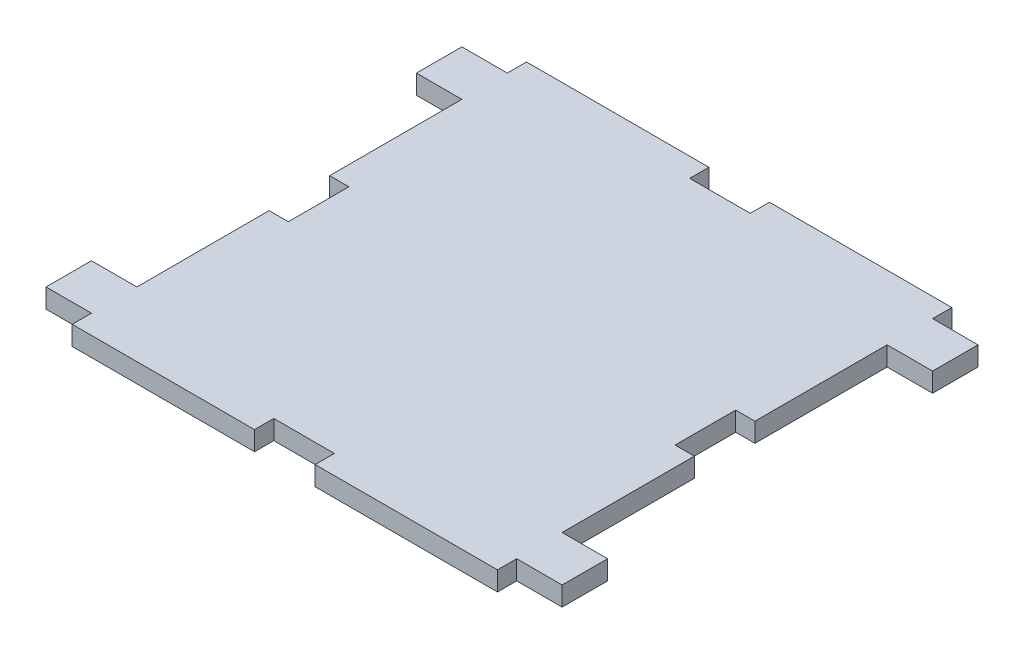
SolidWorks part; units mm, degrees
ref_plane "Front Plane" through (0, 0, 0) normal (0, 0, 1) x (1, 0, 0)
ref_plane "Top Plane" through (0, 0, 0) normal (0, 1, 0) x (1, 0, 0)
ref_plane "Right Plane" through (0, 0, 0) normal (1, 0, 0) x (0, 0, -1)
sketch "Sketch1" plane through (0, 0, 0) normal (0, 1, 0) x (1, 0, 0)
  line L0 (0, 0) -> (0, 150) construction
  line L1 (-140.4, 150) -> (140.4, 150)
  line L2 (-140.4, 150) -> (-140.4, -150)
  line L3 (-140.4, -150) -> (140.4, -150)
  line L4 (140.4, 150) -> (140.4, -150)
  line L5 (0, 0) -> (140.4, 0) construction
  line L6 (-140.4, -107.3) -> (-170.4, -107.3)
  line L7 (140.4, -150) -> (170.4, -150)
  line L8 (140.4, -150) -> (140.4, -107.3)
  line L9 (140.4, -107.3) -> (170.4, -107.3)
  line L10 (170.4, -150) -> (170.4, -107.3)
  line L11 (140.4, 150) -> (170.4, 150)
  line L12 (140.4, 150) -> (140.4, 107.3)
  line L13 (140.4, 107.3) -> (170.4, 107.3)
  line L14 (170.4, 150) -> (170.4, 107.3)
  line L15 (-170.4, -150) -> (-170.4, -107.3)
  line L16 (-140.4, -150) -> (-170.4, -150)
  line L17 (-140.4, -150) -> (-140.4, -107.3)
  line L18 (-140.4, 107.3) -> (-170.4, 107.3)
  line L19 (-170.4, 150) -> (-170.4, 107.3)
  line L20 (-140.4, 150) -> (-170.4, 150)
  line L21 (-140.4, 150) -> (-140.4, 107.3)
  line L22 (-140.4, 137.3) -> (-140.4, 150) construction
  line L23 (140.4, 137.3) -> (140.4, 150) construction
  point P24 (0, 0)
  point P25 (0, 0)
  dimension "D1" = 280.8
  dimension "D2" = 300
  dimension "D3" = 42.7
  dimension "D4" = 30
  dimension "D5" = 30
  dimension "D6" = 42.7
  dimension "D7" = 280.8
extrude "Boss-Extrude1" add sketch "Sketch1" along normal blind 12.7 contours L17 L6 L15 L16 | L21 L18 L19 L20 | L2 L1 L4 L3 | L12 L11 L14 L13 | L8 L7 L10 L9
sketch "Sketch2" plane through (0, 12.7, 0) normal (0, 1, 0) x (1, 0, 0)
  line L0 (140.4, 107.3) -> (140.4, -107.3) construction
  line L1 (140.4, 20) -> (127.7, 20)
  line L2 (140.4, 20) -> (140.4, -20)
  line L3 (140.4, -20) -> (127.7, -20)
  line L4 (127.7, 20) -> (127.7, -20)
  line L5 (170.4, 150) -> (-170.4, 150) construction
  line L7 (0, -6.985) -> (0, 6.985) construction
  line L8 (-140.4, -20) -> (-127.7, -20)
  line L9 (-127.7, 20) -> (-127.7, -20)
  line L10 (-140.4, 20) -> (-127.7, 20)
  line L11 (-140.4, 20) -> (-140.4, -20)
  line L12 (170.4, 150) -> (170.4, 107.3) construction
  line L13 (-20, 150) -> (20, 150)
  line L14 (-20, 150) -> (-20, 137.3)
  line L15 (-20, 137.3) -> (20, 137.3)
  line L16 (20, 150) -> (20, 137.3)
  line L17 (-6.985, 0) -> (6.985, 0) construction
  line L18 (-20, -137.3) -> (20, -137.3)
  line L19 (20, -150) -> (20, -137.3)
  line L20 (-20, -150) -> (20, -150)
  line L21 (-20, -150) -> (-20, -137.3)
  line L23 (140.4, 150) -> (170.4, 150)
  line L24 (140.4, 150) -> (140.4, 137.3)
  line L25 (140.4, 137.3) -> (170.4, 137.3)
  line L26 (170.4, 150) -> (170.4, 137.3)
  line L29 (0, 150) -> (0, -150) construction
  line L30 (-140.4, 0) -> (140.4, 0) construction
  line L31 (-140.4, 137.3) -> (-170.4, 137.3)
  line L32 (-170.4, 150) -> (-170.4, 137.3)
  line L33 (-140.4, 150) -> (-170.4, 150)
  line L34 (-140.4, 150) -> (-140.4, 137.3)
  line L35 (-140.4, -150) -> (-140.4, -137.3)
  line L36 (-140.4, -150) -> (-170.4, -150)
  line L37 (-170.4, -150) -> (-170.4, -137.3)
  line L38 (-140.4, -137.3) -> (-170.4, -137.3)
  line L39 (140.4, -137.3) -> (170.4, -137.3)
  line L40 (170.4, -150) -> (170.4, -137.3)
  line L41 (140.4, -150) -> (170.4, -150)
  line L42 (140.4, -150) -> (140.4, -137.3)
  line M3 (-170.4, -150) -> (170.4, -150)
  dimension "D1" = 40
  dimension "D2" = 12.7
  dimension "D3" = 130
  dimension "D4" = 40
  dimension "D5" = 12.7
  dimension "D6" = 150.4
  dimension "D7" = 12.7
  dimension "D8" = 30
extrude "Cut-Extrude2" cut sketch "Sketch2" against normal up to surface (12.7 mm away) contours L21 L19 L18 M3 | L11 L8 L9 L10 | L2 L3 L4 L1 | L13 L16 L15 L14 | L31 L32 L33 L34 | L24 L23 L26 L25 | L35 L38 L37 L36 | L39 L40 L41 L42 up to face at (0, 0, 0)
